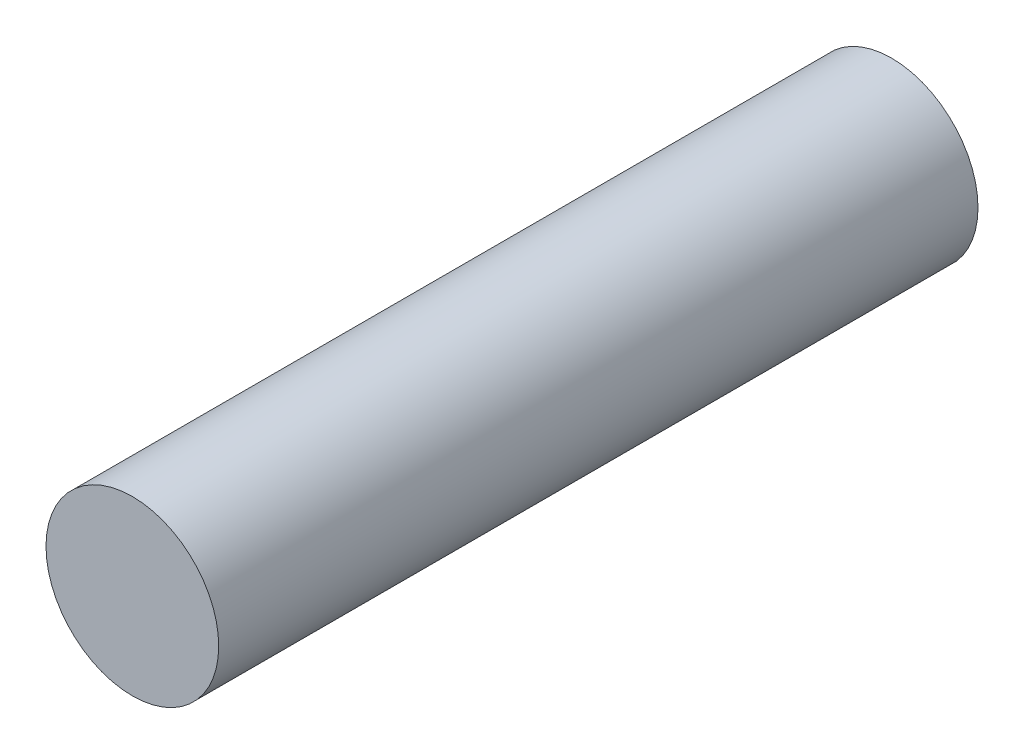
SolidWorks part; units mm, degrees
ref_plane "前视基准面" through (0, 0, 0) normal (0, 0, 1) x (1, 0, 0)
ref_plane "上视基准面" through (0, 0, 0) normal (0, 1, 0) x (1, 0, 0)
ref_plane "右视基准面" through (0, 0, 0) normal (1, 0, 0) x (0, 0, -1)
sketch "草图2" plane through (0, 0, 0) normal (0, 0, 1) x (1, 0, 0)
  circle A0 centre (0.6604, 8.6801) radius 8.075
  dimension "D1" = 16.15
extrude "凸台-拉伸1" add sketch "草图2" along normal blind 71
